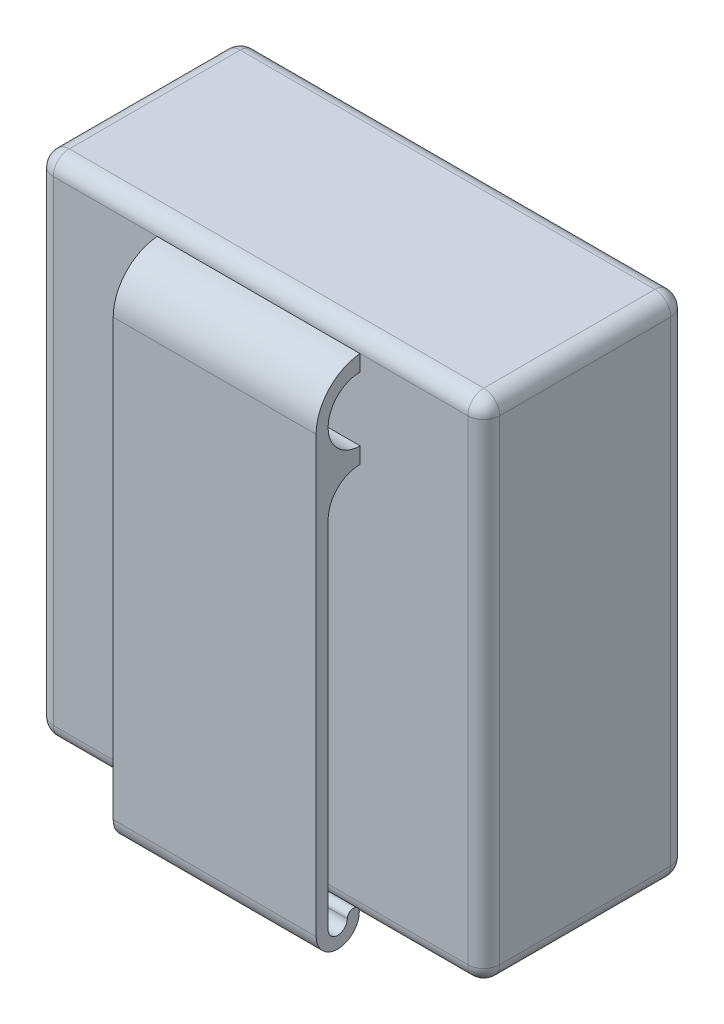
SolidWorks part; units mm, degrees
ref_plane "Front Plane" through (0, 0, 0) normal (0, 0, 1) x (1, 0, 0)
ref_plane "Top Plane" through (0, 0, 0) normal (0, 1, 0) x (1, 0, 0)
ref_plane "Right Plane" through (0, 0, 0) normal (1, 0, 0) x (0, 0, -1)
sketch "Sketch1" plane through (0, 0, 0) normal (0, 0, 1) x (1, 0, 0)
  line L1 (0, 0) -> (55.88, 0)
  line L2 (0, 0) -> (0, 63.5)
  line L3 (0, 63.5) -> (55.88, 63.5)
  line L4 (55.88, 0) -> (55.88, 63.5)
  dimension "D1" = 63.5
  dimension "D2" = 55.88
extrude "Boss-Extrude1" add sketch "Sketch1" along normal blind 25.4
fillet "Fillet1" radius 2 12 edges at (0, 0, 12.7) (55.88, 0, 12.7) (27.94, 0, 0) (55.88, 31.75, 0) (0, 31.75, 0) (55.88, 31.75, 25.4) (27.94, 0, 25.4) (0, 31.75, 25.4) (55.88, 63.5, 12.7) (27.94, 63.5, 25.4) (0, 63.5, 12.7) (27.94, 63.5, 0)
ref_plane "Plane1" through (15, 0, 0) normal (-1, 0, 0) x (0, 0, 1)
sketch "Sketch3" plane through (15, 0, 0) normal (-1, 0, 0) x (0, 0, 1)
  line L0 (25.4, 61.5) -> (25.4, 59.5)
  line L1 (25.4, 61.5) -> (25.4, 2) construction
  line L2 (25.4, 51.5) -> (25.4, 49.5)
  line L3 (29.4, 45.5) -> (29.4, 1.05)
  line L4 (30.9, 1.05) -> (30.9, 55.5)
  arc A0 (25.4, 59.5) -> (25.4, 51.5) centre (25.4, 55.5) cw
  arc A1 (25.4, 49.5) -> (29.4, 45.5) centre (25.4, 45.5) cw
  arc A2 (29.4, 1.05) -> (27, 1.05) centre (28.2, 1.05) cw
  arc A3 (27, 1.05) -> (25.5, 1.05) centre (26.25, 1.05) ccw
  arc A4 (25.5, 1.05) -> (30.9, 1.05) centre (28.2, 1.05) ccw
  arc A5 (30.9, 55.5) -> (25.4, 61.5) centre (24.8773, 55.5) ccw
  dimension "D1" = 4
  dimension "D2" = 0.75
  dimension "D3" = 1.2
  dimension "D4" = 2
  dimension "D5" = 2
  dimension "D6" = 44.45
extrude "Boss-Extrude2" add sketch "Sketch3" against normal blind 25.4
